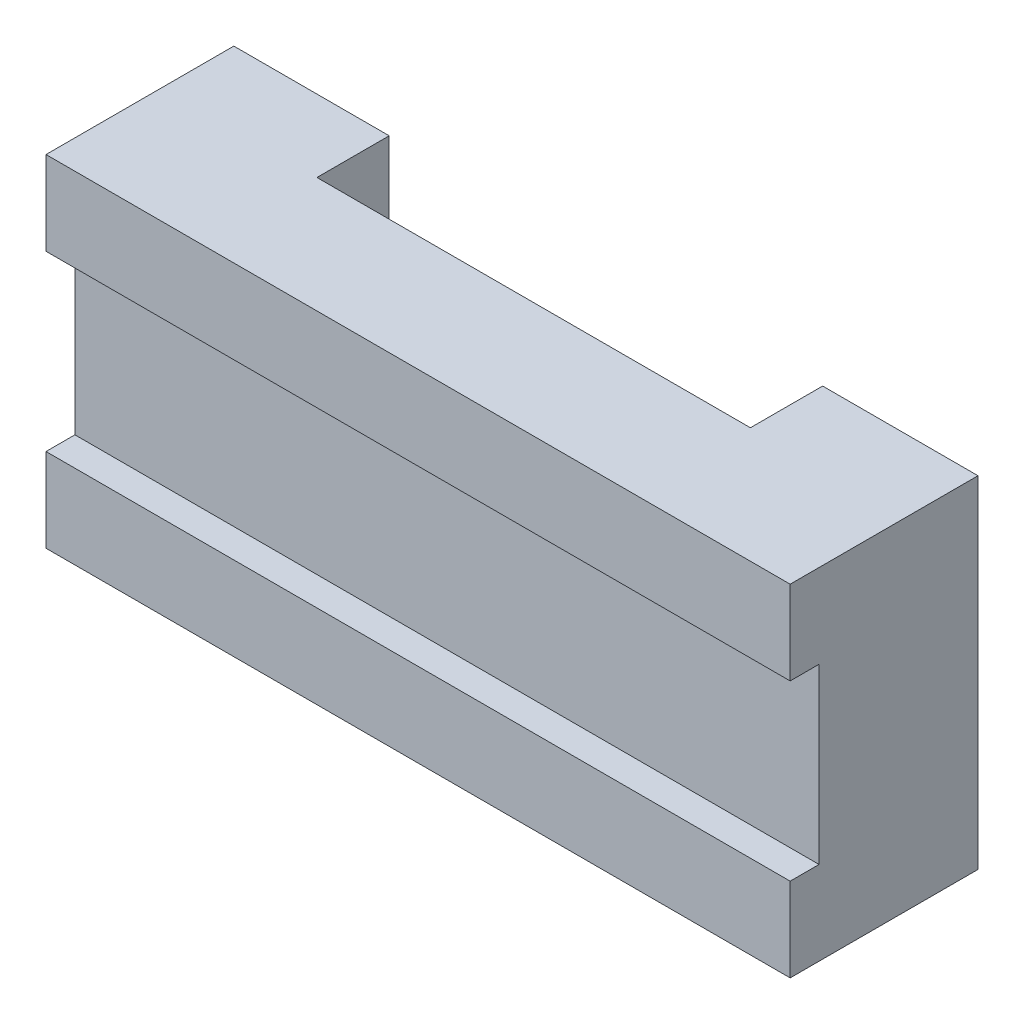
SolidWorks part; units mm, degrees
ref_plane "Alzado" through (0, 0, 0) normal (0, 0, 1) x (1, 0, 0)
ref_plane "Planta" through (0, 0, 0) normal (0, 1, 0) x (1, 0, 0)
ref_plane "Vista lateral" through (0, 0, 0) normal (1, 0, 0) x (0, 0, -1)
sketch "Croquis2" plane through (0, 0, 0) normal (0, 0, 1) x (1, 0, 0)
  line L24 (25.3, 14) -> (25.3, 8.2) construction
  line L48 (18.3, 14) -> (32.3, 14) construction
  line L56 (24, 8.2) -> (75.5028, 8.2)
  line L63 (24, 42) -> (24, 6) construction
  line L64 (75.5028, 6) -> (75.5028, 42.5) construction
  line L65 (74.7, 26) -> (74.7, 31.8) construction
  line L66 (81.7, 26) -> (67.7, 26) construction
  line L67 (24, 31.8) -> (24, 8.2)
  line L68 (24, 31.8) -> (75.5028, 31.8)
  line L69 (75.5028, 31.8) -> (75.5028, 8.2)
  dimension "D1" = 8.2
extrude "Saliente-Extruir1" add sketch "Croquis2" along normal up to vertex (11 mm away)
sketch "Croquis4" plane through (75.5028, 0, 0) normal (1, 0, 0) x (0, 0, -1)
  line L0 (-11, 8.2) -> (-13, 8.2)
  line L1 (-13, 8.2) -> (-13, 14)
  line L2 (-11, 8.2) -> (-11, 14)
  line L3 (-11, 31.8) -> (-13, 31.8)
  line L4 (-13, 31.8) -> (-13, 26)
  line L5 (-11, 26) -> (-11, 31.8)
  line L6 (0, 8.2) -> (0, 31.8) construction
  line L7 (-11, 31.8) -> (0, 31.8) construction
  line L8 (-13, 14) -> (-11, 14)
  line L10 (-13, 26) -> (-11, 26)
  dimension "D1" = 5.8
  dimension "D8" = 13
extrude "Saliente-Extruir2" add sketch "Croquis4" against normal up to vertex (51.5028 mm away)
sketch "Croquis5" plane through (0, 8.2, 0) normal (0, -1, 0) x (1, 0, 0)
  line L0 (75.5028, 13) -> (75.5028, 0) construction
  line L2 (24, 0) -> (75.5028, 0) construction
  line L3 (49.7514, 0) -> (34.7514, 0)
  line L5 (49.7514, 5) -> (34.7514, 5)
  line L6 (34.7514, 0) -> (34.7514, 5)
  line L7 (49.7514, 0) -> (64.7514, 0)
  line L9 (49.7514, 5) -> (64.7514, 5)
  line L10 (64.7514, 0) -> (64.7514, 5)
  dimension "D1" = 10.7514
  dimension "D2" = 5
extrude "Cortar-Extruir1" cut sketch "Croquis5" against normal up to vertex
